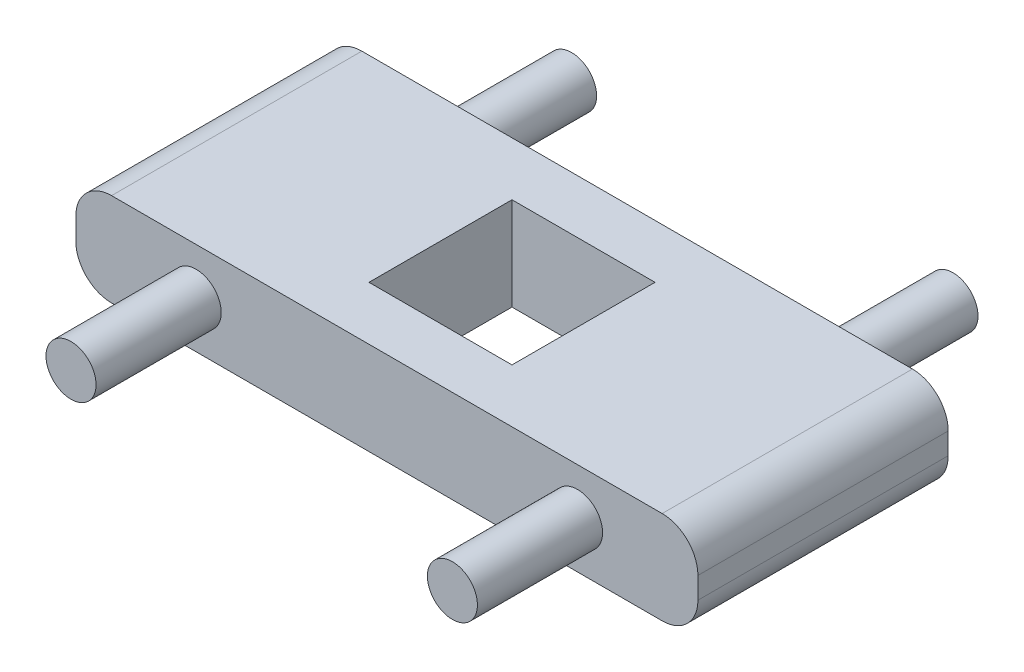
SolidWorks part; units mm, degrees
ref_plane "Front Plane" through (0, 0, 0) normal (0, 0, 1) x (1, 0, 0)
ref_plane "Top Plane" through (0, 0, 0) normal (0, 1, 0) x (1, 0, 0)
ref_plane "Right Plane" through (0, 0, 0) normal (1, 0, 0) x (0, 0, -1)
sketch "Sketch1" plane through (0, 0, 0) normal (0, 1, 0) x (1, 0, 0)
  line L0 (0, 52.4546) -> (0, -48.9446) construction
  line L1 (-55.245, -22.225) -> (55.245, -22.225)
  line L2 (-55.245, -22.225) -> (-55.245, 22.225)
  line L3 (-55.245, 22.225) -> (55.245, 22.225)
  line L4 (55.245, -22.225) -> (55.245, 22.225)
  line L7 (12.7, 12.7) -> (-12.7, 12.7)
  line L8 (12.7, 12.7) -> (12.7, -12.7)
  line L9 (12.7, -12.7) -> (-12.7, -12.7)
  line L10 (-12.7, 12.7) -> (-12.7, -12.7)
  line L11 (12.7, 12.7) -> (-12.7, -12.7) construction
  line L12 (12.7, -12.7) -> (-12.7, 12.7) construction
  point P0 (0, 0)
  point P5 (0, 0)
  point P11 (0, -22.225)
  dimension "D1" = 44.45
  dimension "D2" = 110.49
  dimension "D3" = 22.225
  dimension "D4" = 25.4
extrude "Boss-Extrude1" add sketch "Sketch1" along normal mid plane 16.51
sketch "Sketch2" plane through (0, 0, 22.225) normal (0, 0, 1) x (1, 0, 0)
  line L0 (0, -20.1286) -> (0, 23.6165) construction
  circle A0 centre (-33.8667, 0) radius 4.445
  circle A1 centre (33.8667, 0) radius 4.445
  dimension "D1" = 8.89
  dimension "D2" = 67.7333
fillet "Fillet1" radius 6.35 4 edges at (-55.245, -8.255, 0) (-55.245, 8.255, 0) (55.245, 8.255, 0) (55.245, -8.255, 0)
extrude "Boss-Extrude2" add sketch "Sketch2" along normal blind 22.225
sketch "Sketch3" plane through (0, 0, -22.225) normal (0, 0, -1) x (-1, 0, 0)
  line L0 (0, -20.4327) -> (0, 24.4672) construction
  circle A0 centre (-33.8667, 0) radius 4.445
  circle A1 centre (33.8667, 0) radius 4.445
  dimension "D1" = 8.89
  dimension "D2" = 67.7333
extrude "Boss-Extrude3" add sketch "Sketch3" along normal blind 22.225
